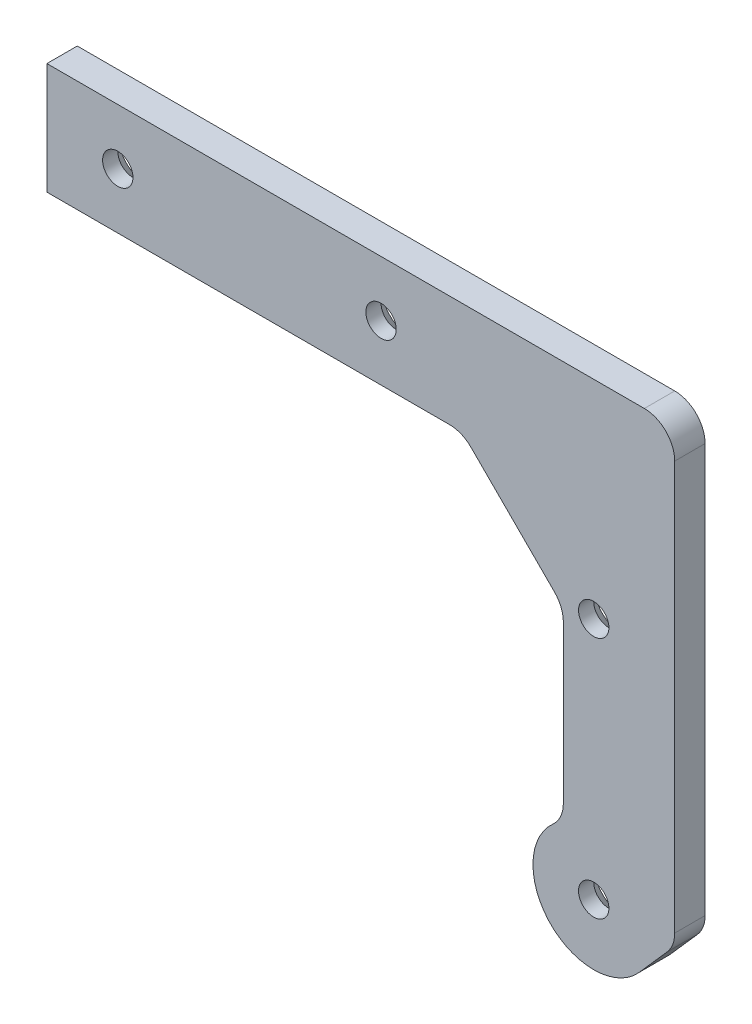
SolidWorks part; units mm, degrees
ref_plane "Спереди" through (0, 0, 0) normal (0, 0, 1) x (1, 0, 0)
ref_plane "Сверху" through (0, 0, 0) normal (0, 1, 0) x (1, 0, 0)
ref_plane "Справа" through (0, 0, 0) normal (1, 0, 0) x (0, 0, -1)
sketch "Эскиз1" plane through (0, 0, 0) normal (0, 0, 1) x (1, 0, 0)
  line L0 (0, 0) -> (-56.5, 0) construction
  line L1 (0, 0) -> (0, -46.5) construction
  line L2 (-56.5, 5.5) -> (-56.5, -5.5)
  line L3 (-56.5, -5.5) -> (-5.5, -5.5)
  line L4 (-5.5, -46.5) -> (5.5, -46.5)
  line L5 (-5.5, -5.5) -> (-5.5, -46.5)
  line L6 (5.5, -46.5) -> (5.5, 5.5)
  line L7 (5.5, 5.5) -> (-56.5, 5.5)
  dimension "D4" = 11
  dimension "D1" = 11
  dimension "D2" = 51
  dimension "D3" = 52
extrude "тело" add sketch "Эскиз1" along normal blind 3
sketch "отверстия" plane through (0, 0, 3) normal (0, 0, 1) x (1, 0, 0)
  line L0 (-56.5, 0) -> (0, 0) construction
  line L1 (-56.5, 5.5) -> (-56.5, -5.5) construction
  line L2 (-2.5, 5.5) -> (-2.5, -46.5) construction
  line L3 (5.5, 5.5) -> (-56.5, 5.5) construction
  line L4 (-5.5, -5.5) -> (-5.5, -46.5) construction
  line L5 (-5.5, -46.5) -> (5.5, -46.5) construction
  circle A0 centre (-49.5, 0) radius 1.5
  circle A1 centre (-23.5, 0) radius 1.5
  circle A2 centre (-2.5, -15) radius 1.5
  circle A3 centre (-2.5, -39) radius 1.5
  dimension "D1" = 3
  dimension "D2" = 21
  dimension "D3" = 26
  dimension "D4" = 15
  dimension "D5" = 39
  dimension "D6" = 3
extrude "отверстия под шурупы" cut sketch "отверстия" against normal through all
sketch "Эскиз3" plane through (0, 0, 3) normal (0, 0, 1) x (1, 0, 0)
  circle A0 centre (-2.5, -39) radius 1.5
  circle A4 centre (-2.5, -39) radius 1.5 construction
  circle A5 centre (-2.5, -39) radius 6
  dimension "D1" = 12
extrude "наплыв" add sketch "Эскиз3" against normal up to surface (3 mm away) up to face at (-48, 0, 0)
sketch "Эскиз4" plane through (0, 0, 3) normal (0, 0, 1) x (1, 0, 0)
  line L0 (-5.5, -46.5) -> (-5.5, -44.1962)
  line L1 (-5.5, -46.5) -> (5.5, -46.5)
  line L2 (-5.5, -46.5) -> (5.5, -46.5) construction
  line L3 (5.5, -46.5) -> (5.5, 5.5) construction
  line L4 (5.5, -46.5) -> (5.5, -39)
  line L5 (5.5, -39) -> (2, -42.9686)
  arc A0 (-5.5, -44.1962) -> (2, -42.9686) centre (-2.5, -39) ccw
  arc A1 (-5.5, -33.8038) -> (-5.5, -44.1962) centre (-2.5, -39) ccw construction
extrude "вырез" cut sketch "Эскиз4" against normal through all
chamfer "Фаска3" distance 10 angle 45 1 edges at (-5.5, -5.5, 1.5)
fillet "Скругление3" radius 3 5 edges at (5.5, 5.5, 1.5) (-5.5, -15.5, 1.5) (-15.5, -5.5, 1.5) (-5.5, -33.8038, 1.5) (5.5, -39, 1.5)
chamfer "Фаска1" [suppressed] distance 1.5 angle 45
chamfer "Фаска2" distance 1.5 angle 45 4 edges at (-1, -39, 0) (-1, -15, 0) (-22, 0, 0) (-48, 0, 0)
